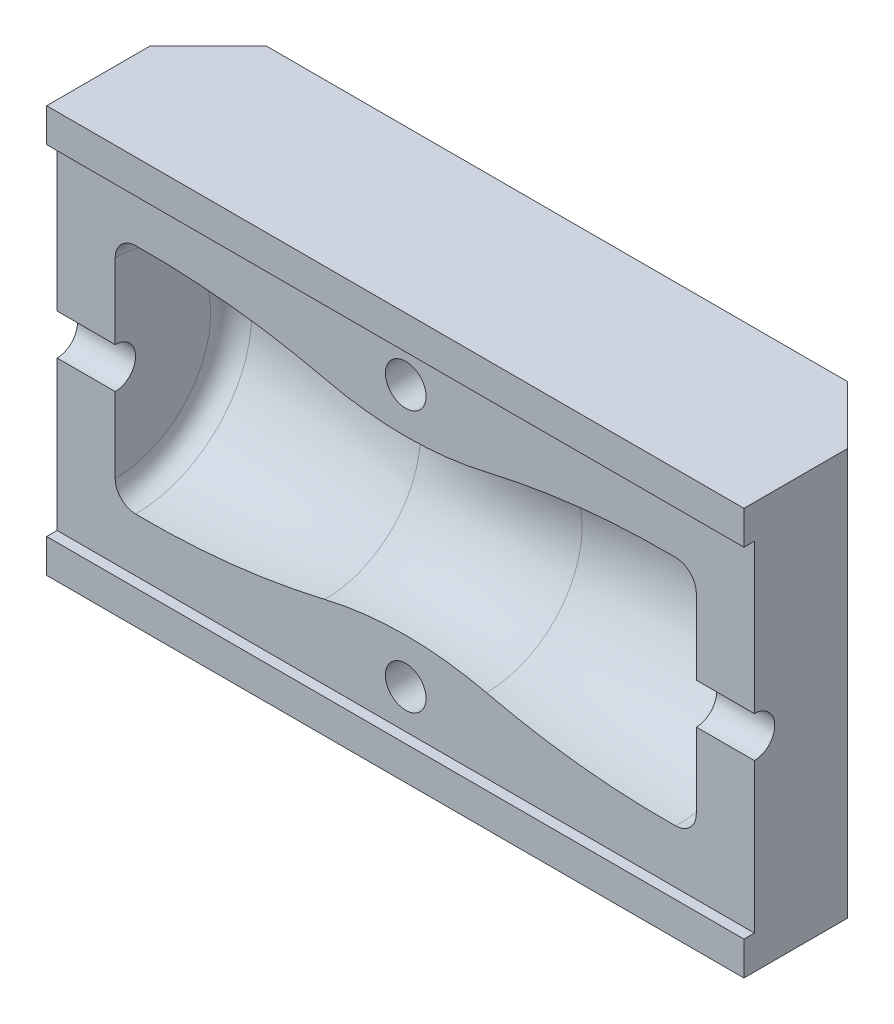
SolidWorks part; units mm, degrees
ref_plane "Front Plane" through (0, 0, 0) normal (0, 0, 1) x (1, 0, 0)
ref_plane "Top Plane" through (0, 0, 0) normal (0, 1, 0) x (1, 0, 0)
ref_plane "Right Plane" through (0, 0, 0) normal (1, 0, 0) x (0, 0, -1)
sketch "Sketch1" plane through (0, 0, 0) normal (0, 0, 1) x (1, 0, 0)
  line L1 (-30, 17.5) -> (30, 17.5)
  line L2 (-30, 17.5) -> (-30, -17.5)
  line L3 (-30, -17.5) -> (30, -17.5)
  line L4 (30, 17.5) -> (30, -17.5)
  line L5 (-30, 17.5) -> (30, -17.5) construction
  line L6 (-30, -17.5) -> (30, 17.5) construction
  point P0 (0, 0)
  dimension "D1" = 35
  dimension "D2" = 60
extrude "Boss-Extrude1" add sketch "Sketch1" along normal blind 13
sketch "Sketch2" plane through (0, 0, 13) normal (0, 0, 1) x (1, 0, 0)
  line L0 (-30, 0) -> (30, 0) construction
  line L1 (-30, 17.5) -> (-30, -17.5) construction
  line L2 (30, -17.5) -> (30, 17.5) construction
  line L3 (-25, 0) -> (-25, 8.2181)
  line L4 (-6.9483, 8.2181) -> (6.9483, 8.2181) construction
  line L5 (0, 8.2181) -> (0, 0) construction
  line L6 (25, 8.2181) -> (25, 0)
  line L7 (25, 0) -> (-25, 0)
  line L8 (-25, 8.2181) -> (25, 8.2181) construction
  line L9 (23.2433, 10) -> (-23.2433, 10) construction
  arc A0 (-25, 8.2181) -> (-23.2433, 10) centre (-23.2179, 8.2181) cw
  arc A1 (-23.2433, 10) -> (-6.9483, 8.2181) centre (-22.2956, -56.7322) cw
  arc A2 (-6.9483, 8.2181) -> (6.9483, 8.2181) centre (0, 37.6237) ccw
  arc A3 (6.9483, 8.2181) -> (23.2433, 10) centre (22.2956, -56.7322) cw
  arc A4 (23.2433, 10) -> (25, 8.2181) centre (23.2179, 8.2181) cw
  dimension "D3" = 1.7821
  dimension "D1" = 50
  dimension "D2" = 10
revolve "Cut-Revolve1" cut sketch "Sketch2" angle 360 about L7
sketch "Sketch3" plane through (30, 0, 0) normal (1, 0, 0) x (0, 0, -1)
  line L0 (-13, -17.5) -> (-13, 17.5) construction
  circle A0 centre (-13, 0) radius 1.75
  dimension "D1" = 3.5
extrude "Cut-Extrude1" cut sketch "Sketch3" against normal through all both
sketch "Sketch4" plane through (0, 0, 13) normal (0, 0, 1) x (1, 0, 0)
  line L0 (30, 1.75) -> (30, 17.5) construction
  line L1 (-30, 17.5) -> (30, 17.5)
  line L2 (-30, 17.5) -> (-30, 14.6)
  line L3 (-30, 14.6) -> (30, 14.6)
  line L4 (30, 17.5) -> (30, 14.6)
  line L5 (-30, -1.75) -> (-30, -17.5) construction
  line L6 (30, -17.5) -> (-30, -17.5)
  line L7 (30, -17.5) -> (30, -14.6)
  line L8 (30, -14.6) -> (-30, -14.6)
  line L9 (-30, -17.5) -> (-30, -14.6)
  dimension "D1" = 2.9
sketch "Sketch5" plane through (0, 0, 13) normal (0, 0, 1) x (1, 0, 0)
  line L0 (0, 11.25) -> (0, -11.25) construction
  circle A0 centre (0, 11.25) radius 1.75
  circle A1 centre (0, -11.25) radius 1.75
  dimension "D1" = 3.5
  dimension "D2" = 22.5
extrude "Cut-Extrude3" cut sketch "Sketch5" against normal through all
chamfer "Chamfer1" distance 5 angle 45 2 edges at (30, 0, 0) (-30, 0, 0)
sketch "Sketch6" plane through (0, 0, 0) normal (0, 0, -1) x (-1, 0, 0)
  line L1 (3.4641, 11.25) -> (1.7321, 14.25)
  line L2 (1.7321, 14.25) -> (-1.7321, 14.25)
  line L3 (-1.7321, 14.25) -> (-3.4641, 11.25)
  line L4 (-3.4641, 11.25) -> (-1.7321, 8.25)
  line L5 (-1.7321, 8.25) -> (1.7321, 8.25)
  line L6 (1.7321, 8.25) -> (3.4641, 11.25)
  line L7 (3.4641, -11.25) -> (1.7321, -8.25)
  line L8 (1.7321, -8.25) -> (-1.7321, -8.25)
  line L9 (-1.7321, -8.25) -> (-3.4641, -11.25)
  line L10 (-3.4641, -11.25) -> (-1.7321, -14.25)
  line L11 (-1.7321, -14.25) -> (1.7321, -14.25)
  line L12 (1.7321, -14.25) -> (3.4641, -11.25)
  circle A0 centre (0, 11.25) radius 3 construction
  circle A1 centre (0, -11.25) radius 3 construction
  dimension "D1" = 6
extrude "Cut-Extrude4" cut sketch "Sketch6" against normal blind 7
extrude "Boss-Extrude2" add sketch "Sketch4" along normal blind 0.9
chamfer "Chamfer2" distance 0.5 angle 45 26 edges at (-2.5981, -9.75, 0) (-2.5981, 12.75, 0) (-1.75, 11.25, 7) (0, 8.25, 7) (2.5981, 9.75, 7) (2.5981, 12.75, 7) (0, 14.25, 7) (-2.5981, 12.75, 7) (-2.5981, 9.75, 7) (-1.75, -11.25, 7) (0, -14.25, 7) (2.5981, -12.75, 7) (2.5981, -9.75, 7) (0, -8.25, 7) (-2.5981, -9.75, 7) (-2.5981, -12.75, 7) (-2.5981, -12.75, 0) (0, -14.25, 0) (2.5981, -12.75, 0) (2.5981, -9.75, 0) (0, -8.25, 0) (-2.5981, 9.75, 0) (0, 8.25, 0) (2.5981, 9.75, 0) (2.5981, 12.75, 0) (0, 14.25, 0)
